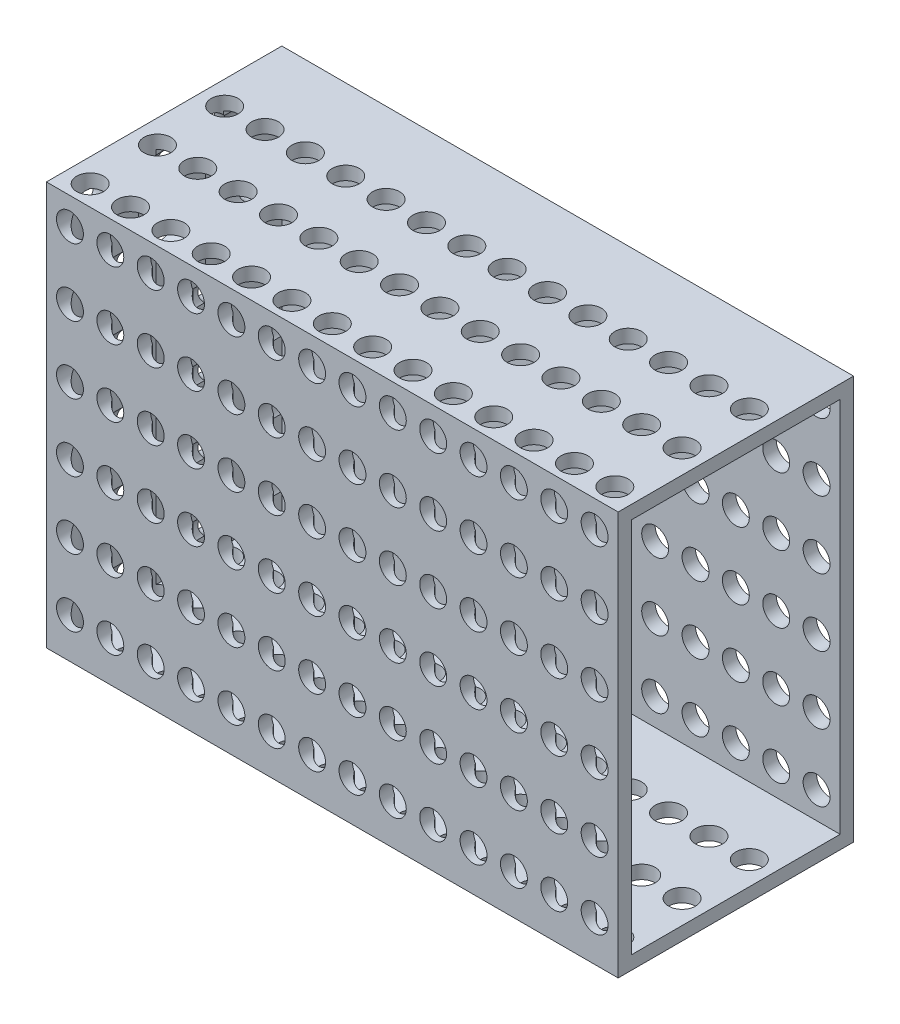
SolidWorks part; units mm, degrees
ref_plane "Alzado" through (0, 0, 0) normal (0, 0, 1) x (1, 0, 0)
ref_plane "Planta" through (0, 0, 0) normal (0, 1, 0) x (1, 0, 0)
ref_plane "Vista lateral" through (0, 0, 0) normal (1, 0, 0) x (0, 0, -1)
sketch "Croquis2" plane through (0, 0, 0) normal (0, 0, 1) x (1, 0, 0)
  line L1 (-42.5, -30) -> (42.5, -30)
  line L2 (-42.5, -30) -> (-42.5, 30)
  line L3 (-42.5, 30) -> (42.5, 30)
  line L4 (42.5, -30) -> (42.5, 30)
  line L5 (-42.5, -30) -> (42.5, 30) construction
  line L6 (-42.5, 30) -> (42.5, -30) construction
  point P0 (0, 0)
  dimension "D1" = 85
  dimension "D2" = 60
extrude "Saliente-Extruir1" add sketch "Croquis2" along normal blind 35
shell "Vaciado1" thickness 2
sketch "Croquis3" plane through (0, 0, 35) normal (0, 0, 1) x (1, 0, 0)
  circle A0 centre (-39, 26) radius 2
  circle A1 centre (-33, 26) radius 2
  circle A2 centre (-27, 26) radius 2
  circle A3 centre (-21, 26) radius 2
  circle A4 centre (-15, 26) radius 2
  circle A5 centre (-9, 26) radius 2
  circle A6 centre (-3, 26) radius 2
  circle A7 centre (3, 26) radius 2
  circle A8 centre (9, 26) radius 2
  circle A9 centre (15, 26) radius 2
  circle A10 centre (21, 26) radius 2
  circle A11 centre (27, 26) radius 2
  circle A12 centre (33, 26) radius 2
  circle A13 centre (39, 26) radius 2
  circle A14 centre (-33, 16) radius 2
  circle A15 centre (-27, 16) radius 2
  circle A16 centre (-21, 16) radius 2
  circle A17 centre (-15, 16) radius 2
  circle A18 centre (-9, 16) radius 2
  circle A19 centre (-3, 16) radius 2
  circle A20 centre (3, 16) radius 2
  circle A21 centre (9, 16) radius 2
  circle A22 centre (15, 16) radius 2
  circle A23 centre (21, 16) radius 2
  circle A24 centre (27, 16) radius 2
  circle A25 centre (33, 16) radius 2
  circle A26 centre (39, 16) radius 2
  circle A27 centre (-33, 6) radius 2
  circle A28 centre (-27, 6) radius 2
  circle A29 centre (-21, 6) radius 2
  circle A30 centre (-15, 6) radius 2
  circle A31 centre (-9, 6) radius 2
  circle A32 centre (-3, 6) radius 2
  circle A33 centre (3, 6) radius 2
  circle A34 centre (9, 6) radius 2
  circle A35 centre (15, 6) radius 2
  circle A36 centre (21, 6) radius 2
  circle A37 centre (27, 6) radius 2
  circle A38 centre (33, 6) radius 2
  circle A39 centre (39, 6) radius 2
  circle A40 centre (-33, -4) radius 2
  circle A41 centre (-27, -4) radius 2
  circle A42 centre (-21, -4) radius 2
  circle A43 centre (-15, -4) radius 2
  circle A44 centre (-9, -4) radius 2
  circle A45 centre (-3, -4) radius 2
  circle A46 centre (3, -4) radius 2
  circle A47 centre (9, -4) radius 2
  circle A48 centre (15, -4) radius 2
  circle A49 centre (21, -4) radius 2
  circle A50 centre (27, -4) radius 2
  circle A51 centre (33, -4) radius 2
  circle A52 centre (39, -4) radius 2
  circle A53 centre (-33, -14) radius 2
  circle A54 centre (-27, -14) radius 2
  circle A55 centre (-21, -14) radius 2
  circle A56 centre (-15, -14) radius 2
  circle A57 centre (-9, -14) radius 2
  circle A58 centre (-3, -14) radius 2
  circle A59 centre (3, -14) radius 2
  circle A60 centre (9, -14) radius 2
  circle A61 centre (15, -14) radius 2
  circle A62 centre (21, -14) radius 2
  circle A63 centre (27, -14) radius 2
  circle A64 centre (33, -14) radius 2
  circle A65 centre (39, -14) radius 2
  circle A66 centre (-33, -24) radius 2
  circle A67 centre (-27, -24) radius 2
  circle A68 centre (-21, -24) radius 2
  circle A69 centre (-15, -24) radius 2
  circle A70 centre (-9, -24) radius 2
  circle A71 centre (-3, -24) radius 2
  circle A72 centre (3, -24) radius 2
  circle A73 centre (9, -24) radius 2
  circle A74 centre (15, -24) radius 2
  circle A75 centre (21, -24) radius 2
  circle A76 centre (27, -24) radius 2
  circle A77 centre (33, -24) radius 2
  circle A78 centre (39, -24) radius 2
  circle A79 centre (-39, 16) radius 2
  circle A80 centre (-39, 6) radius 2
  circle A81 centre (-39, -4) radius 2
  circle A82 centre (-39, -14) radius 2
  circle A83 centre (-39, -24) radius 2
  dimension "D3" = 4
  dimension "D1" = 26
  dimension "D2" = 39
  dimension "D4" = 14
  dimension "D5" = 6
extrude "Cortar-Extruir1" cut sketch "Croquis3" against normal blind 35
sketch "Croquis4" plane through (0, -30, 0) normal (0, -1, 0) x (1, 0, 0)
  circle A0 centre (-39, 32) radius 2
  circle A1 centre (-33, 32) radius 2
  circle A2 centre (-27, 32) radius 2
  circle A3 centre (-21, 32) radius 2
  circle A4 centre (-15, 32) radius 2
  circle A5 centre (-9, 32) radius 2
  circle A6 centre (-3, 32) radius 2
  circle A7 centre (3, 32) radius 2
  circle A8 centre (9, 32) radius 2
  circle A9 centre (15, 32) radius 2
  circle A10 centre (21, 32) radius 2
  circle A11 centre (27, 32) radius 2
  circle A12 centre (33, 32) radius 2
  circle A13 centre (39, 32) radius 2
  circle A14 centre (-33, 22) radius 2
  circle A15 centre (-27, 22) radius 2
  circle A16 centre (-21, 22) radius 2
  circle A17 centre (-15, 22) radius 2
  circle A18 centre (-9, 22) radius 2
  circle A19 centre (-3, 22) radius 2
  circle A20 centre (3, 22) radius 2
  circle A21 centre (9, 22) radius 2
  circle A22 centre (15, 22) radius 2
  circle A23 centre (21, 22) radius 2
  circle A24 centre (27, 22) radius 2
  circle A25 centre (33, 22) radius 2
  circle A26 centre (39, 22) radius 2
  circle A27 centre (-33, 12) radius 2
  circle A28 centre (-27, 12) radius 2
  circle A29 centre (-21, 12) radius 2
  circle A30 centre (-15, 12) radius 2
  circle A31 centre (-9, 12) radius 2
  circle A32 centre (-3, 12) radius 2
  circle A33 centre (3, 12) radius 2
  circle A34 centre (9, 12) radius 2
  circle A35 centre (15, 12) radius 2
  circle A36 centre (21, 12) radius 2
  circle A37 centre (27, 12) radius 2
  circle A38 centre (33, 12) radius 2
  circle A39 centre (39, 12) radius 2
  circle A40 centre (-39, 22) radius 2
  circle A41 centre (-39, 12) radius 2
  dimension "D2" = 32
  dimension "D3" = 4
  dimension "D1" = 39
  dimension "D4" = 14
  dimension "D5" = 3
extrude "Cortar-Extruir2" cut sketch "Croquis4" against normal blind 65
sketch "Croquis5" plane through (-42.5, 0, 0) normal (-1, 0, 0) x (0, 0, 1)
  line L0 (0, 30) -> (0, -30) construction
  circle A0 centre (30, 26) radius 2
  circle A1 centre (24, 26) radius 2
  circle A2 centre (18, 26) radius 2
  circle A3 centre (12, 26) radius 2
  circle A4 centre (6, 26) radius 2
  circle A5 centre (24, 16) radius 2
  circle A6 centre (18, 16) radius 2
  circle A7 centre (12, 16) radius 2
  circle A8 centre (6, 16) radius 2
  circle A9 centre (24, 6) radius 2
  circle A10 centre (18, 6) radius 2
  circle A11 centre (12, 6) radius 2
  circle A12 centre (6, 6) radius 2
  circle A13 centre (24, -4) radius 2
  circle A14 centre (18, -4) radius 2
  circle A15 centre (12, -4) radius 2
  circle A16 centre (6, -4) radius 2
  circle A17 centre (24, -14) radius 2
  circle A18 centre (18, -14) radius 2
  circle A19 centre (12, -14) radius 2
  circle A20 centre (6, -14) radius 2
  circle A21 centre (24, -24) radius 2
  circle A22 centre (18, -24) radius 2
  circle A23 centre (12, -24) radius 2
  circle A24 centre (6, -24) radius 2
  circle A25 centre (30, 16) radius 2
  circle A26 centre (30, 6) radius 2
  circle A27 centre (30, -4) radius 2
  circle A28 centre (30, -14) radius 2
  circle A29 centre (30, -24) radius 2
  point P5 (0, 0)
  dimension "D2" = 26
  dimension "D3" = 4
  dimension "D1" = 30
  dimension "D4" = 5
  dimension "D5" = 6
extrude "Cortar-Extruir3" cut sketch "Croquis5" against normal blind 5
